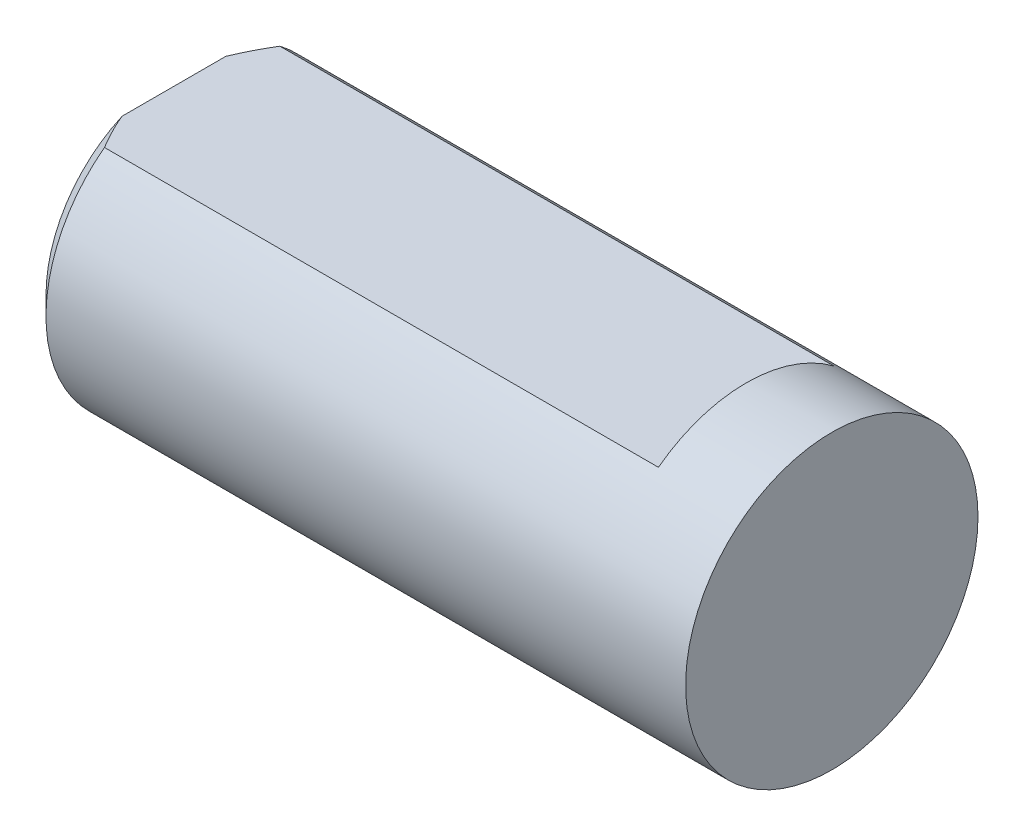
SolidWorks part; units mm, degrees
ref_plane "Plan1" through (0, 0, 0) normal (0, 0, 1) x (1, 0, 0)
ref_plane "Plan2" through (0, 0, 0) normal (0, 1, 0) x (1, 0, 0)
ref_plane "Plan3" through (0, 0, 0) normal (1, 0, 0) x (0, 0, -1)
sketch "Esquisse1" plane through (0, 0, 0) normal (0, 0, 1) x (1, 0, 0)
  line L0 (-18, 0) -> (-18, 4)
  line L1 (-18, 4) -> (0, 4)
  line L2 (0, 4) -> (0, 0)
  line L5 (0, 0) -> (-40, 0) construction
  line L6 (-18, 0) -> (0, 0)
  dimension "D1" = 18
  dimension "D2" = 8
revolve "Base-Révolution" add sketch "Esquisse1" angle 360 about L5
chamfer "Chanfrein1" distance 0.5 angle 45 1 edges at (-18, 0, -4)
sketch "Esquisse2" plane through (0, 0, 0) normal (0, 0, 1) x (1, 0, 0)
  line L0 (0, 4) -> (-17.5, 4) construction
  line L1 (-2.3438, 12.9027) -> (-19.6612, 12.9027)
  line L2 (-2.3438, 12.9027) -> (-2.3438, 3.2)
  line L3 (-2.3438, 3.2) -> (-19.6612, 3.2)
  line L4 (-19.6612, 12.9027) -> (-19.6612, 3.2)
  dimension "D1" = 0.8
extrude "Enlèv. mat.-Extru.1" cut sketch "Esquisse2" against normal through all and the other way through all
